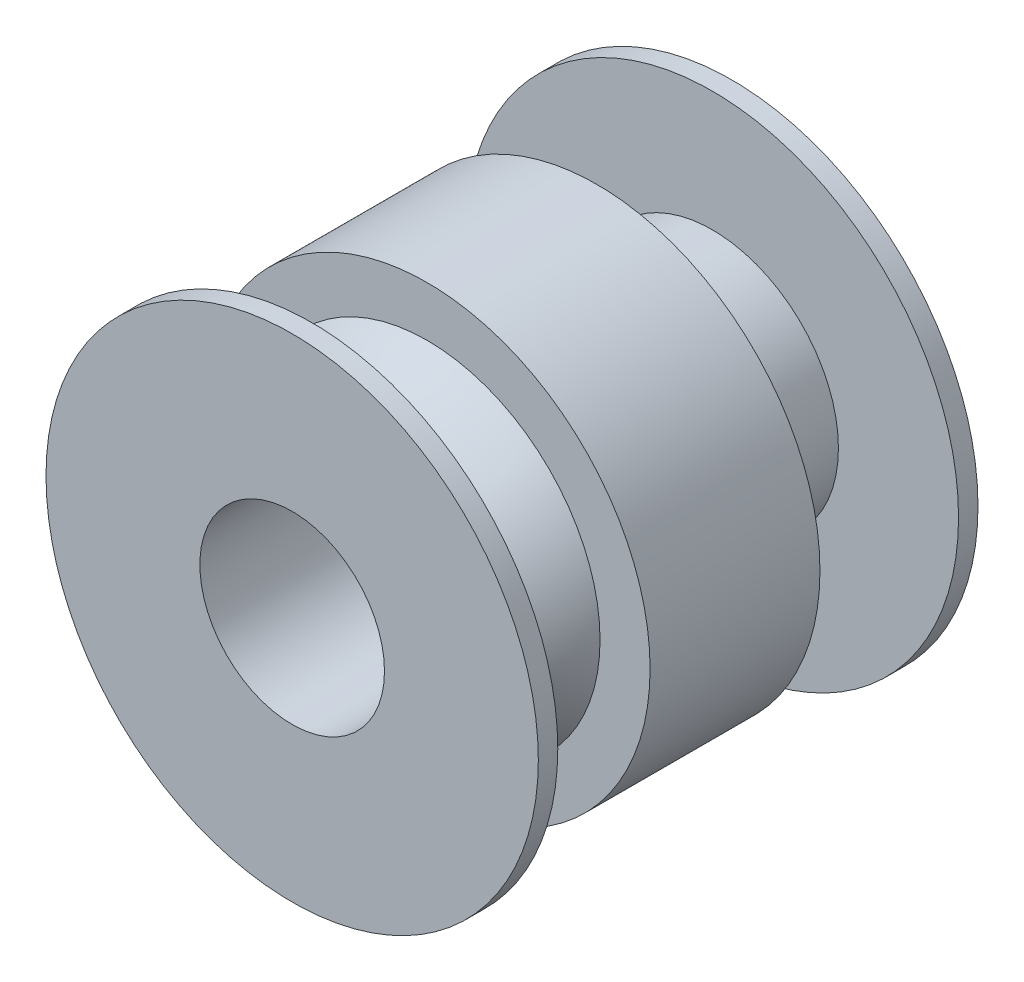
SolidWorks part; units mm, degrees
material "Alloy Steel"
ref_plane "X-Y Datum" through (0, 0, 0) normal (0, 0, 1) x (1, 0, 0)
ref_plane "X-Z Datum" through (0, 0, 0) normal (0, 1, 0) x (1, 0, 0)
ref_plane "Y-Z Datum" through (0, 0, 0) normal (1, 0, 0) x (0, 0, -1)
sketch "Sketch1" plane through (0, 0, 0) normal (1, 0, 0) x (0, 0, -1)
  line L0 (82.1362, -22.0492) -> (50082.1362, -22.0492) construction
  line L1 (71.12, -5.2479) -> (71.12, 49994.7521) construction
  line L2 (66.7385, -30.973) -> (71.12, -22.0492) construction
  line L3 (71.12, -22.0492) -> (63.6, -28.5516) construction
  line L4 (60.7822, -26.8117) -> (81.4578, -26.8117)
  line L5 (60.7822, -28.5516) -> (63.6, -28.5516)
  line L6 (66.7385, -30.973) -> (66.7385, -33.5554)
  line L7 (66.7385, -33.5554) -> (75.5015, -33.5554)
  line L8 (75.5015, -33.5554) -> (75.5015, -30.973)
  line L11 (78.64, -28.5516) -> (81.4578, -28.5516)
  line L28 (81.4578, -28.5516) -> (81.4578, -26.8117) construction
  line L31 (60.7822, -28.5516) -> (60.7822, -34.7492)
  line L32 (60.7822, -34.7492) -> (59.7789, -34.7492)
  line L33 (59.7789, -34.7492) -> (59.7789, -26.8117)
  line L34 (59.7789, -26.8117) -> (60.7822, -26.8117)
  line L35 (81.4578, -28.5516) -> (81.4578, -34.7492)
  line L36 (81.4578, -34.7492) -> (82.4611, -34.7492)
  line L37 (82.4611, -34.7492) -> (82.4611, -26.8117)
  line L38 (82.4611, -26.8117) -> (81.4578, -26.8117)
  arc A0 (63.6, -28.5516) -> (66.7385, -30.973) centre (71.12, -22.0492) ccw
  arc A1 (75.5015, -30.973) -> (78.64, -28.5516) centre (71.12, -22.0492) ccw
  point P8 (71.12, -26.8117)
  point P15 (71.12, -33.5554)
  point P22 (0, 0)
  dimension "D1" = 9.525
  dimension "D3" = 8.763
  dimension "D5" = 23
  dimension "D2" = 13.0048
  dimension "D4" = 20.6756
  dimension "D6" = 23.0124
  dimension "D7" = 22.6822
  dimension "D8" = 25.4
  dimension "D9" = 22.6822
revolve "Revolve1" add sketch "Sketch1" angle 360 about L0
